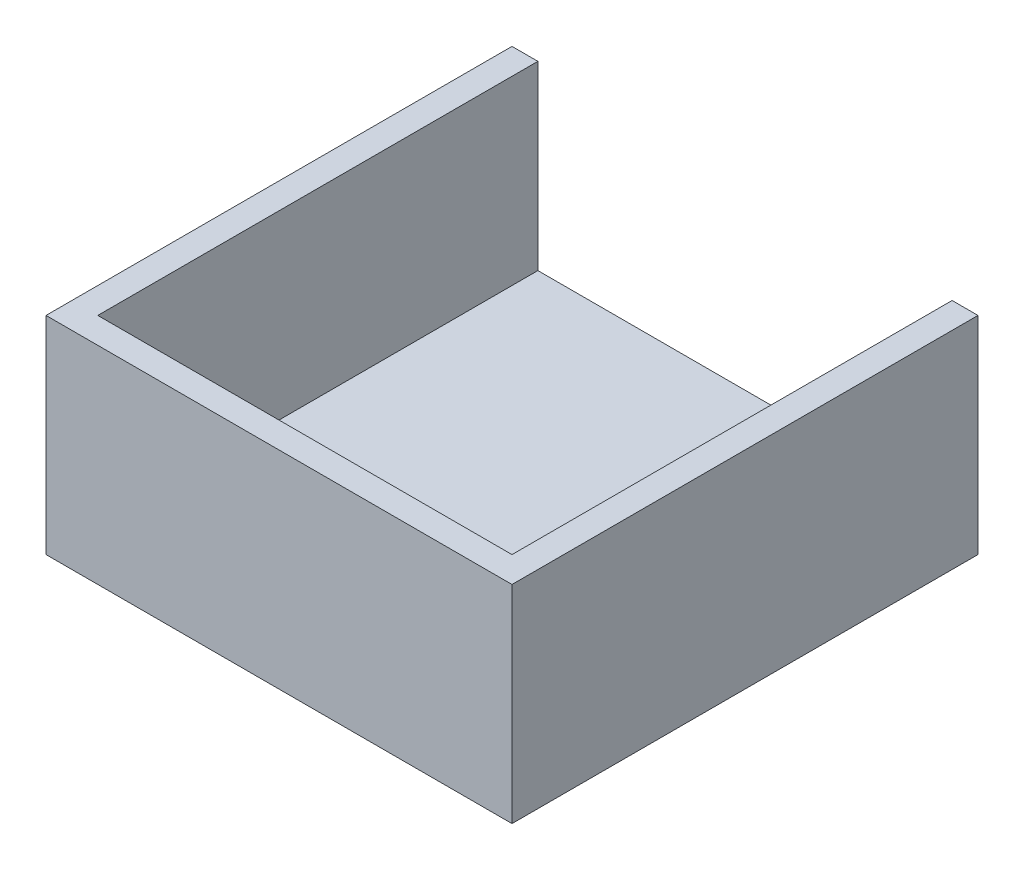
SolidWorks part; units mm, degrees
ref_plane "정면" through (0, 0, 0) normal (0, 0, 1) x (1, 0, 0)
ref_plane "윗면" through (0, 0, 0) normal (0, 1, 0) x (1, 0, 0)
ref_plane "우측면" through (0, 0, 0) normal (1, 0, 0) x (0, 0, -1)
sketch "스케치1" plane through (0, 0, 0) normal (0, 1, 0) x (1, 0, 0)
  line L0 (0, 73.84) -> (0, -73.84) construction
  line L2 (9, -9) -> (-9, -9)
  line L3 (9, -9) -> (9, 9)
  line L4 (9, 9) -> (-9, 9)
  line L5 (-9, -9) -> (-9, 9)
  line L6 (9, -9) -> (-9, 9) construction
  line L7 (9, 9) -> (-9, -9) construction
  point P3 (0, 0)
  dimension "D1" = 18
  dimension "D2" = 18
extrude "보스-돌출1" add sketch "스케치1" along normal blind 8
sketch "스케치5" plane through (0, 0, 0) normal (0, 1, 0) x (1, 0, 0)
  line L0 (-9, 9) -> (-9, -9) construction
  line L1 (-8, 9) -> (8, 9)
  line L2 (-8, 9) -> (-8, -8)
  line L3 (-8, -8) -> (8, -8)
  line L4 (8, 9) -> (8, -8)
  line L5 (9, 9) -> (-9, 9) construction
  dimension "D1" = 16
  dimension "D2" = 1
  dimension "D3" = 17
extrude "컷-돌출6" cut sketch "스케치5" against normal blind 7 from surface at 8 starting at face at (0, 8, 0)
sketch "스케치6" plane through (0, 0, 0) normal (0, 1, 0) x (1, 0, 0)
  line L1 (9, -9) -> (-9, -9)
  line L2 (9, -9) -> (9, 9)
  line L3 (9, 9) -> (-9, 9)
  line L4 (-9, -9) -> (-9, 9)
  line L5 (9, -9) -> (-9, 9) construction
  line L6 (9, 9) -> (-9, -9) construction
  point P0 (0, 0)
extrude "보스-돌출2" add sketch "스케치6" along normal blind 1 from offset 8 separate body
sketch "스케치7" plane through (0, 0, 0) normal (0, 1, 0) x (1, 0, 0)
  line L1 (9, 9) -> (-9, 9) construction
  circle A0 centre (0, -0.5) radius 6.5
  dimension "D1" = 3
  dimension "D2" = 13
extrude "컷-돌출7" cut sketch "스케치7" against normal blind 1 from surface at 9 starting at face at (0, 9, 0)
sketch "스케치10" plane through (0, 9, 0) normal (0, 1, 0) x (1, 0, 0)
  line L4 (-9, 9) -> (-9, -9)
  line L5 (-9, -9) -> (9, -9)
  line L6 (9, -9) -> (9, 9)
  line L7 (9, 9) -> (-9, 9)
  line L8 (-9, 9) -> (-9, -9)
  line L9 (-9, -9) -> (9, -9)
  line L10 (9, -9) -> (9, 9)
  line L11 (9, 9) -> (-9, 9)
  dimension "D1" = 0
extrude "컷-돌출8" cut sketch "스케치10" against normal blind 1
